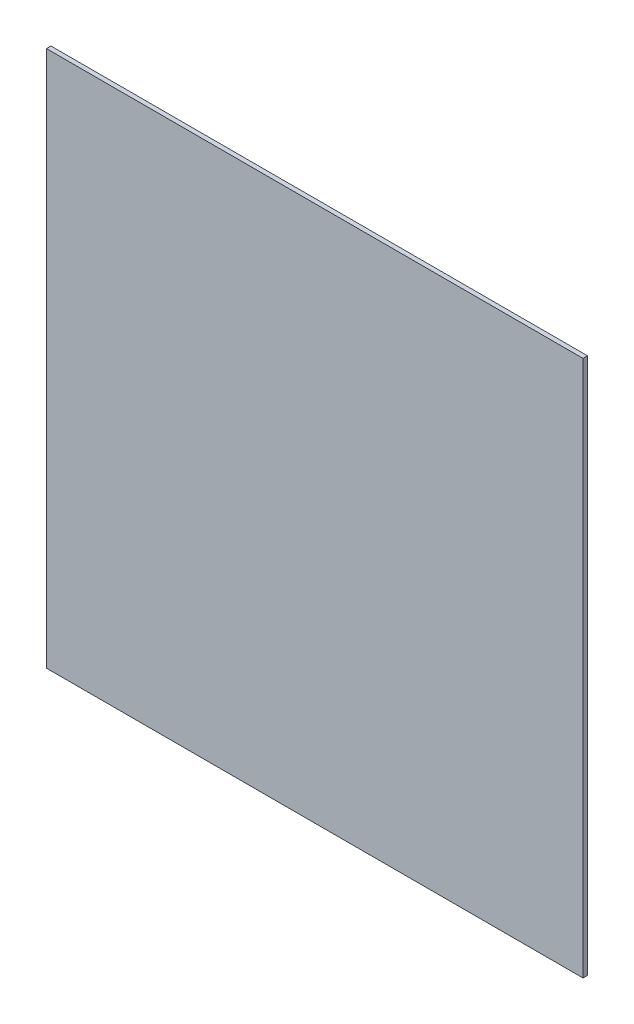
SolidWorks part; units mm, degrees
ref_plane "Alzado" through (0, 0, 0) normal (0, 0, 1) x (1, 0, 0)
ref_plane "Planta" through (0, 0, 0) normal (0, 1, 0) x (1, 0, 0)
ref_plane "Vista lateral" through (0, 0, 0) normal (1, 0, 0) x (0, 0, -1)
sketch "Croquis1" plane through (0, 0, 0) normal (0, 0, 1) x (1, 0, 0)
  line L0 (0, -55) -> (0, 55) construction
  line L1 (-59.69, 59.69) -> (59.69, 59.69)
  line L2 (-59.69, 59.69) -> (-59.69, -59.69)
  line L3 (-59.69, -59.69) -> (59.69, -59.69)
  line L4 (59.69, 59.69) -> (59.69, -59.69)
  line L5 (55, 0) -> (-55, 0) construction
  point P4 (-59.69, 0)
  point P5 (0, 59.69)
  dimension "D1" = 119.38
  dimension "D2" = 119.38
extrude "Saliente-Extruir1" add sketch "Croquis1" along normal mid plane 1
